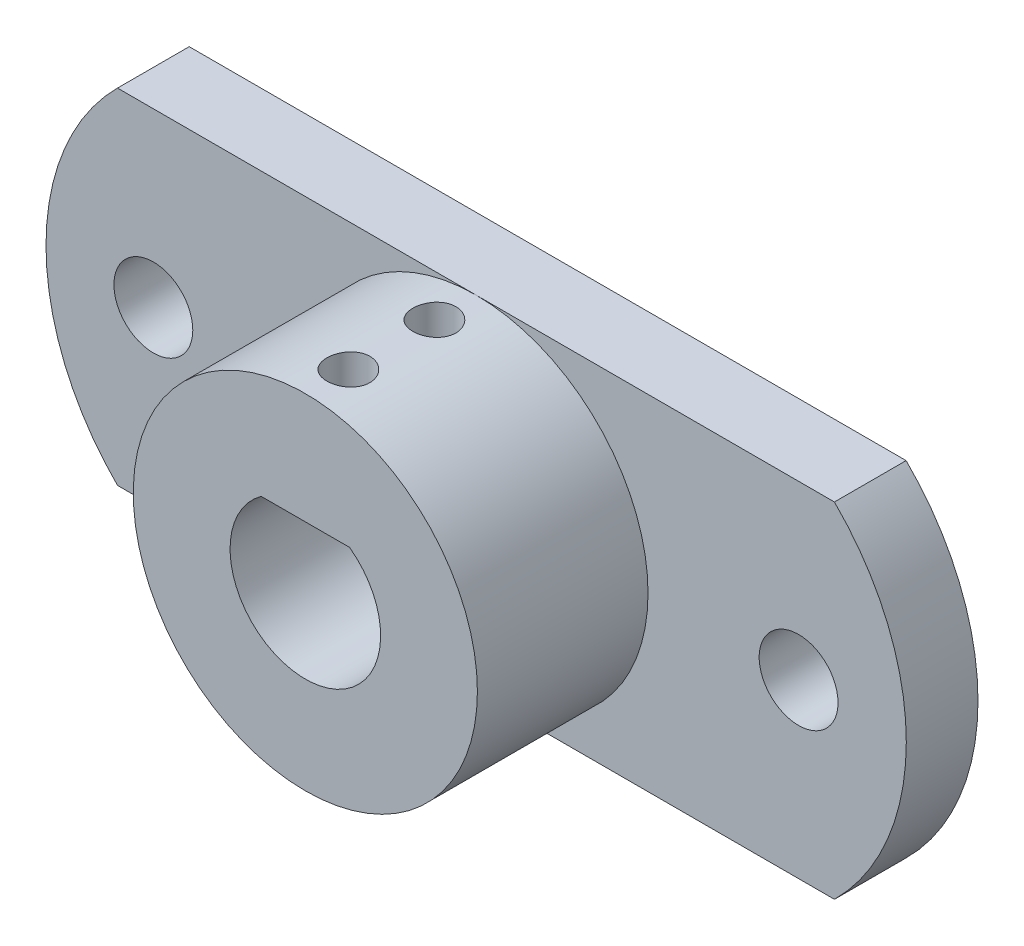
SolidWorks part; units mm, degrees
material "1060 合金"
ref_plane "前视基准面" through (0, 0, 0) normal (0, 0, 1) x (1, 0, 0)
ref_plane "上视基准面" through (0, 0, 0) normal (0, 1, 0) x (1, 0, 0)
ref_plane "右视基准面" through (0, 0, 0) normal (1, 0, 0) x (0, 0, -1)
sketch "草图1" plane through (0, 0, 0) normal (0, 0, 1) x (1, 0, 0)
  line L0 (-25, 0) -> (25, 0)
  line L1 (-25, -24) -> (25, -24)
  line L2 (-22.5, -12) -> (22.5, -12) construction
  arc A0 (-25, 0) -> (-25, -24) centre (-13.0565, -12) ccw
  arc A1 (25, -24) -> (25, 0) centre (13.1433, -12) ccw
  circle A2 centre (-22.5, -12) radius 2.75
  circle A3 centre (22.5, -12) radius 2.75
  point P9 (0, -12)
  point P10 (0, 0)
  point P11 (0, 0)
  point P12 (0, 0)
  point P13 (0, 0)
  point P14 (0, -24)
  point P15 (0, 0)
  point P16 (0, 0)
  point P17 (0, 0)
  point P18 (-29.9872, -12)
  point P19 (30.0128, -12)
  point P22 (-14.9817, -12)
  point P23 (10.7775, -12)
  point P24 (-13.0565, -12)
  dimension "D3" = 5.5
  dimension "D1" = 60
  dimension "D2" = 24
  dimension "D4" = 45
  dimension "D5" = 12
  dimension "D6" = 12
  dimension "D7" = 50
extrude "凸台-拉伸1" add sketch "草图1" along normal mid plane 5
sketch "草图2" plane through (0, 0, 2.5) normal (0, 0, 1) x (1, 0, 0)
  circle A0 centre (0, -12) radius 12
  arc A1 (25, -24) -> (25, 0) centre (13.1433, -12) ccw construction
  point P2 (0, 0)
  point P6 (30.0128, -12)
  point P7 (0, 0)
  dimension "D1" = 24
extrude "凸台-拉伸2" add sketch "草图2" along normal blind 11.9
sketch "草图3" plane through (0, 0, 14.4) normal (0, 0, 1) x (1, 0, 0)
  line L0 (-3.0822, -7.75) -> (3.0822, -7.75)
  arc A0 (-3.0822, -7.75) -> (3.0822, -7.75) centre (0, -12) ccw
  dimension "D1" = 10.5
  dimension "D2" = 4.25
extrude "切除-拉伸1" cut sketch "草图3" against normal blind 11.9
sketch "草图4" plane through (0, -7.75, 0) normal (0, -1, 0) x (1, 0, 0)
  line L0 (5.25, 14.4) -> (-5.25, 14.4) construction
  circle A0 centre (0, 11.4) radius 1.5
  circle A1 centre (0, 5.4) radius 1.5
  point P4 (0, 0)
  point P5 (0, 0)
  point P6 (0, 0)
  point P7 (0, 0)
  dimension "D1" = 3
  dimension "D2" = 3
  dimension "D3" = 6
extrude "切除-拉伸2" cut sketch "草图4" against normal through all
